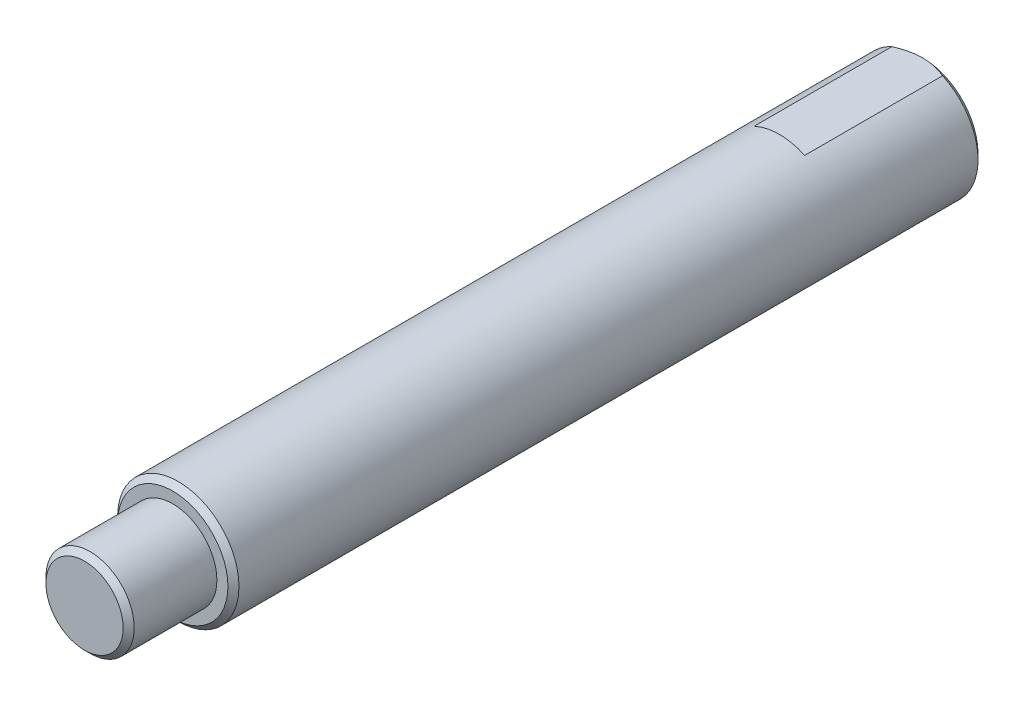
SolidWorks part; units mm, degrees
material "Q235A"
ref_plane "前视基准面" through (0, 0, 0) normal (0, 0, 1) x (1, 0, 0)
ref_plane "上视基准面" through (0, 0, 0) normal (0, 1, 0) x (1, 0, 0)
ref_plane "右视基准面" through (0, 0, 0) normal (1, 0, 0) x (0, 0, -1)
sketch "草图1" plane through (0, 0, 0) normal (0, 0, 1) x (1, 0, 0)
  circle A0 centre (0, 0) radius 5.5
  dimension "D1" = 11
extrude "拉伸1" add sketch "草图1" along normal blind 68
chamfer "倒角1" distance 0.5 angle 45 2 edges at (5.5, 0, 0) (5.5, 0, 68)
sketch "草图2" plane through (0, 0, 68) normal (0, 0, 1) x (1, 0, 0)
  circle A0 centre (0, 0) radius 4
  dimension "D1" = 8
extrude "拉伸2" add sketch "草图2" along normal blind 8
cosmetic thread "装饰螺纹线1" parameters "D2"=7
chamfer "倒角2" distance 0.5 angle 45 1 edges at (4, 0, 76)
hole_wizard "M5 螺纹孔1" positions "草图4" profile "草图3" tap size "M5" standard "GB"
sketch "草图4" plane through (0, 0, 0) normal (0, 0, -1) x (-1, 0, 0)
  point P1 (0, 0)
sketch "草图3" plane through (0, 0, 0) normal (1, 0, 0) x (0, 1, 0)
  line L0 (0, 0) -> (0, 13.6618)
  line L1 (0, 13.6618) -> (2.1, 12.4)
  line L2 (2.1, 12.4) -> (2.1, 0)
  line L5 (2.1, 0) -> (0, 0)
  line L10 (0, 13.6618) -> (-2.1, 12.4) construction
  line L11 (0, -6.35) -> (0, 107.95) construction
  dimension "螺纹孔钻头直径" = 4.2
  dimension "螺纹孔钻头深度" = 12.4
  dimension "导头角度" = 118
cosmetic thread "孔螺蚊线1" parameters "D1"=10, "D2"=5
chamfer "倒角3" distance 0.5 angle 45 1 edges at (-2.1, 0, 0)
sketch "草图5" plane through (0, 0, 0) normal (0, 0, 1) x (1, 0, 0)
  line L0 (0, 0) -> (0, 5) construction
  line L1 (-5, 8) -> (5, 8)
  line L2 (-5, 8) -> (-5, 5)
  line L3 (-5, 5) -> (5, 5)
  line L4 (5, 8) -> (5, 5)
  dimension "D1" = 5
  dimension "D2" = 3
  dimension "D3" = 10
extrude "拉伸3" cut sketch "草图5" along normal blind 13
mirror "镜向1" about plane through (0, 0, 0) normal (0, 1, 0) of "拉伸3"
